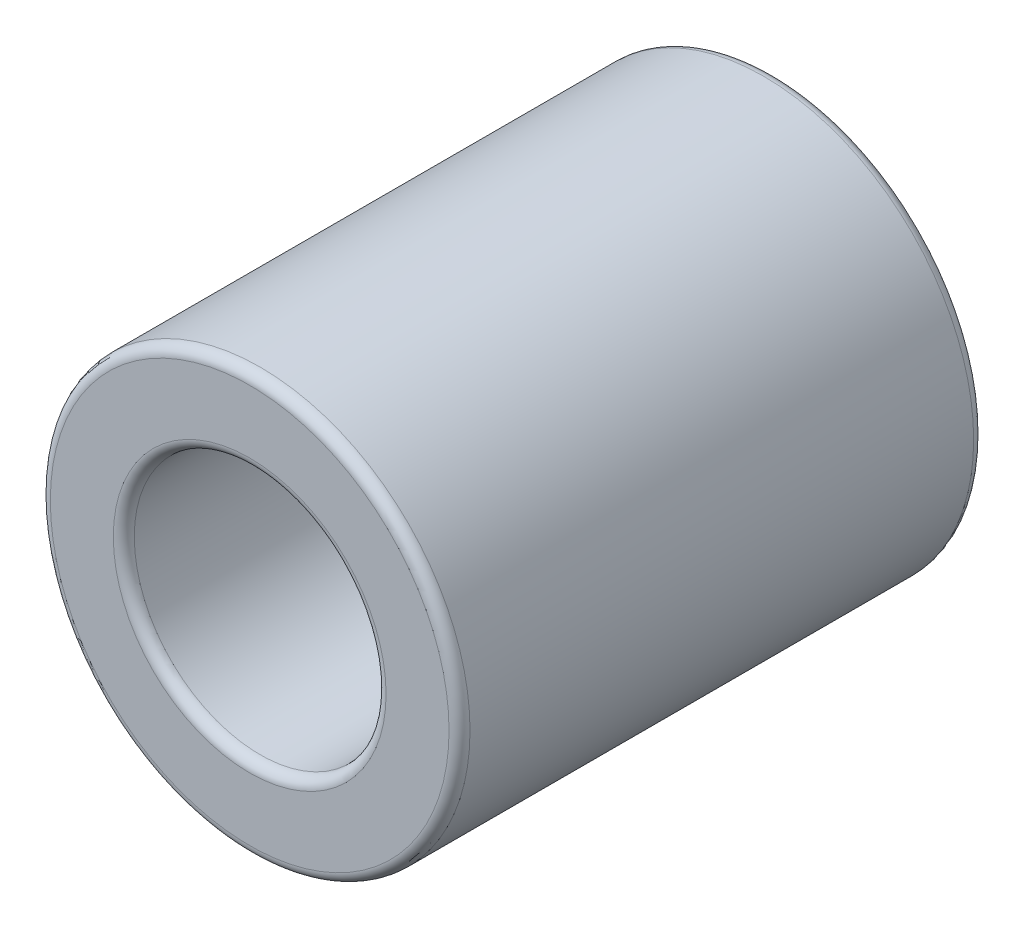
SolidWorks part; units mm, degrees
ref_plane "前视基准面" through (0, 0, 0) normal (0, 0, 1) x (1, 0, 0)
ref_plane "上视基准面" through (0, 0, 0) normal (0, 1, 0) x (1, 0, 0)
ref_plane "右视基准面" through (0, 0, 0) normal (1, 0, 0) x (0, 0, -1)
other "Configuration Table"
sketch "草图1" plane through (0, 0, 0) normal (0, 0, 1) x (1, 0, 0)
  circle A0 centre (0, 0) radius 10
  dimension "D1" = 20
extrude "凸台-拉伸1" add sketch "草图1" along normal blind 25
sketch "草图2" plane through (0, 0, 25) normal (0, 0, 1) x (1, 0, 0)
  circle A0 centre (0, 0) radius 6
  dimension "D1" = 12
extrude "切除-拉伸1" cut sketch "草图2" against normal blind 12.5
sketch "草图3" plane through (0, 0, 0) normal (0, 0, -1) x (-1, 0, 0)
  circle A0 centre (0, 0) radius 3
  dimension "D1" = 6
extrude "切除-拉伸2" cut sketch "草图3" against normal blind 15
fillet "圆角1" radius 0.5 4 edges at (-3, 0, 0) (6, 0, 25) (10, 0, 0) (10, 0, 25)
